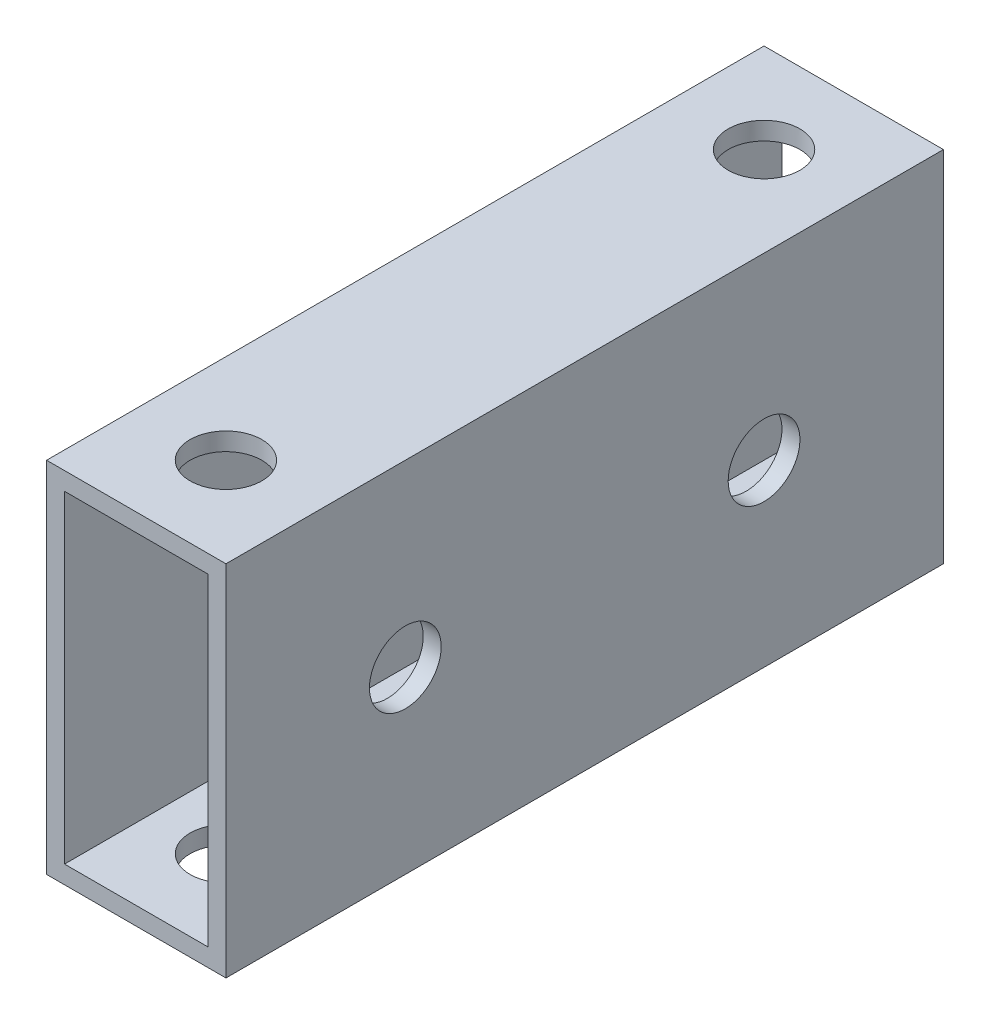
SolidWorks part; units mm, degrees
ref_plane "正面" through (0, 0, 0) normal (0, 0, 1) x (1, 0, 0)
ref_plane "平面" through (0, 0, 0) normal (0, 1, 0) x (1, 0, 0)
ref_plane "右側面" through (0, 0, 0) normal (1, 0, 0) x (0, 0, -1)
sketch "ｽｹｯﾁ1" plane through (0, 0, 0) normal (0, 0, 1) x (1, 0, 0)
  line L1 (5, -10) -> (-5, -10)
  line L2 (5, -10) -> (5, 10)
  line L3 (5, 10) -> (-5, 10)
  line L4 (-5, -10) -> (-5, 10)
  line L5 (5, -10) -> (-5, 10) construction
  line L6 (5, 10) -> (-5, -10) construction
  point P0 (0, 0)
  dimension "D1" = 10
  dimension "D2" = 20
extrude "押し出し-薄板1" add sketch "ｽｹｯﾁ1" along normal blind 40 thin
sketch "ｽｹｯﾁ2" plane through (-5, 0, 0) normal (-1, 0, 0) x (0, 0, 1)
  line L0 (0, 0) -> (40, 0) construction
  line L1 (40, 10) -> (40, -10) construction
  line L2 (20, 10) -> (20, -10) construction
  line L3 (40, 10) -> (0, 10) construction
  line L4 (40, -10) -> (0, -10) construction
  circle A0 centre (10, 0) radius 2
  circle A1 centre (30, 0) radius 2
  dimension "D1" = 20
  dimension "D2" = 4
extrude "ｶｯﾄ - 押し出し1" cut sketch "ｽｹｯﾁ2" against normal through all
sketch "ｽｹｯﾁ3" plane through (0, 10, 0) normal (0, 1, 0) x (1, 0, 0)
  line L0 (0, 0) -> (0, -40) construction
  line L1 (5, -40) -> (-5, -40) construction
  line L2 (5, 0) -> (-5, 0) construction
  line L3 (-5, -20) -> (5, -20) construction
  line L4 (-5, -40) -> (-5, 0) construction
  line L5 (5, -40) -> (5, 0) construction
  circle A0 centre (0, -5) radius 2
  circle A1 centre (0, -35) radius 2
  dimension "D1" = 5
  dimension "D2" = 4
extrude "ｶｯﾄ - 押し出し2" cut sketch "ｽｹｯﾁ3" against normal through all
